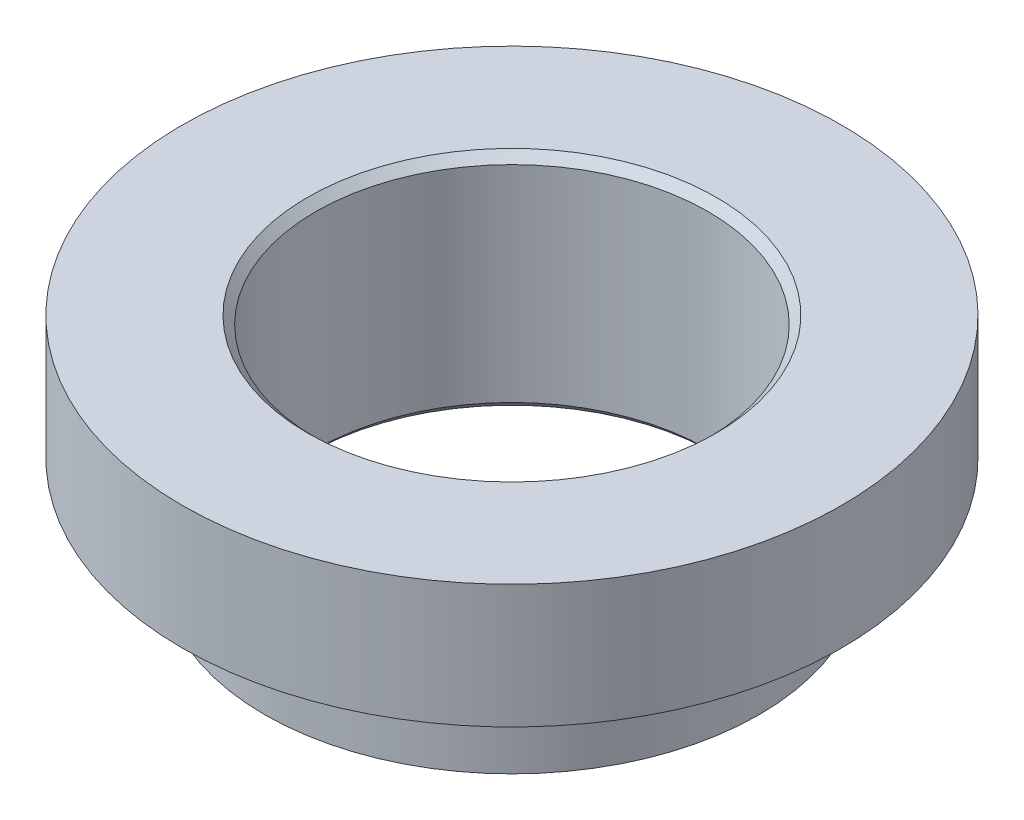
SolidWorks part; units mm, degrees
ref_plane "Plan de face" through (0, 0, 0) normal (0, 0, 1) x (1, 0, 0)
ref_plane "Plan de dessus" through (0, 0, 0) normal (0, 1, 0) x (1, 0, 0)
ref_plane "Plan de droite" through (0, 0, 0) normal (1, 0, 0) x (0, 0, -1)
sketch "Esquisse1" plane through (0, 0, 0) normal (0, 0, 1) x (1, 0, 0)
  line L0 (0, 0) -> (0, -60.2875) construction
  line L1 (-12.4, 0) -> (-20, 0)
  line L2 (-20, 0) -> (-20, -7.5)
  line L3 (-20, -7.5) -> (-15, -7.5)
  line L4 (-15, -7.5) -> (-15, -13.5)
  line L5 (-15, -13.5) -> (-12.4, -13.5)
  line L6 (-11.9, -0.5) -> (-11.9, -13)
  line L7 (-12.4, 0) -> (-11.9, -0.5)
  line L8 (-11.9, -13) -> (-12.4, -13.5)
  point P3 (-11.9, 0)
  point P9 (-11.9, -13.5)
  dimension "D1" = 40
  dimension "D2" = 23.8
  dimension "D3" = 30
  dimension "D4" = 13.5
  dimension "D5" = 6
  dimension "D8" = 0.5
  dimension "D9" = 0.5
revolve "Révolution1" add sketch "Esquisse1" angle 360 about L0
